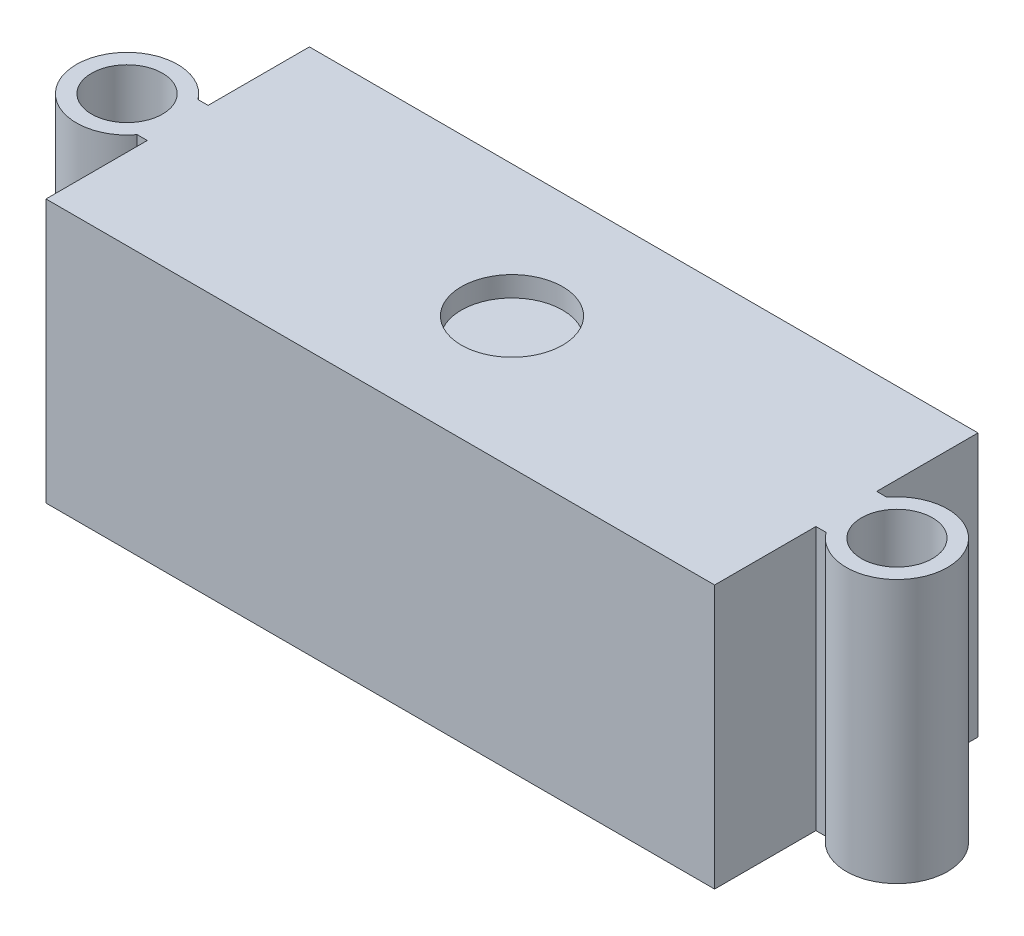
SolidWorks part; units mm, degrees
ref_plane "Front Plane" through (0, 0, 0) normal (0, 0, 1) x (1, 0, 0)
ref_plane "Top Plane" through (0, 0, 0) normal (0, 1, 0) x (1, 0, 0)
ref_plane "Right Plane" through (0, 0, 0) normal (1, 0, 0) x (0, 0, -1)
sketch "Sketch1" plane through (0, 0, 0) normal (0, 0, 1) x (1, 0, 0)
  line L0 (-15, 1.5) -> (-15, 8.5) construction
  line L1 (-15, 0) -> (15, 0)
  line L2 (-15, 0) -> (-15, 1.5)
  line L3 (-15, 10) -> (15, 10)
  line L4 (15, 0) -> (15, 1.5)
  line L5 (-15, 8.5) -> (-15, 10)
  line L6 (15, 1.5) -> (15, 8.5) construction
  line L7 (15, 8.5) -> (15, 10)
  arc A0 (15, 8.5) -> (15, 1.5) centre (15, 5) ccw
  arc A1 (-15, 1.5) -> (-15, 8.5) centre (-15, 5) ccw
  point P5 (0, 0)
  point P12 (0, 0)
  point P13 (0, 0)
  dimension "D3" = 1.5
  dimension "D1" = 10
  dimension "D2" = 30
  dimension "D4" = 1.5
  dimension "D5" = 5
extrude "Boss-Extrude2" add sketch "Sketch1" along normal blind 10
ref_plane "Plane1" through (0, 0, -0.5) normal (0, 0, -1) x (-1, 0, 0)
sketch "Sketch2" plane through (0, 0, -0.5) normal (0, 0, -1) x (-1, 0, 0)
  line L0 (-15.5, 10.5) -> (0, 10.5)
  line L1 (-15.5, 10.5) -> (-15.5, 8)
  line L2 (-15.5, 2) -> (-15.5, -0.5)
  line L3 (-15.5, -0.5) -> (0, -0.5)
  line L4 (-15, 2) -> (-15.5, 2)
  line L5 (-15, 8) -> (-15.5, 8)
  line L6 (15, 0) -> (15, 1.5)
  line L7 (-15, 0) -> (15, 0)
  line L8 (-15, 1.5) -> (-15, 0)
  line L9 (-15, 10) -> (-15, 8.5)
  line L10 (15, 10) -> (-15, 10)
  line L11 (15, 8.5) -> (15, 10)
  line L12 (15, 0) -> (15, 1.5)
  line L13 (-15, 0) -> (15, 0)
  line L14 (-15, 1.5) -> (-15, 0)
  line L15 (-15, 10) -> (-15, 8.5)
  line L16 (15, 10) -> (-15, 10)
  line L17 (15, 8.5) -> (15, 10)
  line L18 (-16.5, -1.5) -> (0, -1.5)
  line L19 (-16.5, 3) -> (-16.5, -1.5)
  line L20 (-15, 3) -> (-16.5, 3)
  line L21 (-15, 7) -> (-16.5, 7)
  line L22 (-16.5, 11.5) -> (-16.5, 7)
  line L23 (-16.5, 11.5) -> (0, 11.5)
  line L24 (0, 5.5) -> (0, -5.5) construction
  line L25 (16.5, 3) -> (16.5, -1.5)
  line L26 (16.5, -1.5) -> (0, -1.5)
  line L27 (15.5, -0.5) -> (0, -0.5)
  line L28 (15.5, 2) -> (15.5, -0.5)
  line L29 (15, 3) -> (16.5, 3)
  line L30 (15, 2) -> (15.5, 2)
  line L31 (15, 7) -> (16.5, 7)
  line L32 (15, 8) -> (15.5, 8)
  line L33 (16.5, 11.5) -> (16.5, 7)
  line L34 (15.5, 10.5) -> (15.5, 8)
  line L35 (16.5, 11.5) -> (0, 11.5)
  line L36 (15.5, 10.5) -> (0, 10.5)
  line L37 (-15.5, -0.5) -> (0.1388, -0.5) construction
  line L38 (-16.5, -1.5) -> (0.1388, -1.5) construction
  line L39 (16.5, 7) -> (16.5, 3)
  line L40 (-16.5, 7) -> (-16.5, 3)
  arc A0 (-15, 2) -> (-15, 8) centre (-15, 5) ccw
  arc A1 (-15, 3) -> (-15, 7) centre (-15, 5) ccw
  arc A2 (-15, 1.5) -> (-15, 8.5) centre (-15, 5) ccw
  arc A3 (15, 8.5) -> (15, 1.5) centre (15, 5) ccw
  arc A4 (-15, 1.5) -> (-15, 8.5) centre (-15, 5) ccw
  arc A5 (15, 8.5) -> (15, 1.5) centre (15, 5) ccw
  arc A6 (15, 3) -> (15, 7) centre (15, 5) cw
  arc A7 (15, 2) -> (15, 8) centre (15, 5) cw
  dimension "D4" = 0.5
  dimension "D7" = 1
  dimension "D2" = 0.5
  dimension "D3" = 0.5
  dimension "D5" = 0.5
  dimension "D6" = 0.5
  dimension "D1" = 0
extrude "Boss-Extrude3" add sketch "Sketch2" against normal blind 11 separate body contours L29 A6 L31 L33 L35 L23 L22 L21 A1 L20 L19 L18 L26 L25 A7 L30 L28 L27 L3 L2 L4 A0 L5 L1 L0 L36 L34 L32 | A6 L29 L39 L31 | L20 A1 L21 L40
sketch "Sketch3" plane through (16.5, 0, 0) normal (1, 0, 0) x (0, 0, -1)
  line L17 (0.5, 11.5) -> (1.5, 11.5)
  line L18 (0.5, 11.5) -> (0.5, -1.5)
  line L19 (0.5, -1.5) -> (1.5, -1.5)
  line L20 (1.5, 11.5) -> (1.5, -1.5)
  line L21 (-10.5, 11.5) -> (-11.5, 11.5)
  line L22 (-10.5, 11.5) -> (-10.5, -1.5)
  line L23 (-10.5, -1.5) -> (-11.5, -1.5)
  line L24 (-11.5, 11.5) -> (-11.5, -1.5)
  point P10 (0, 0)
  dimension "D1" = 1
  dimension "D2" = 1
extrude "Boss-Extrude4" add sketch "Sketch3" against normal blind 33
sketch "Sketch4" plane through (0, 11.5, 0) normal (0, 1, 0) x (1, 0, 0)
  line L0 (-16.5, -11.5) -> (-16.5, 1.5) construction
  line L1 (-16.5, -11.5) -> (-16.5, 1.5) construction
  line L2 (0, -7.15) -> (0, 7.15) construction
  line L3 (16.5, -6.5) -> (17.1, -6.5)
  line L4 (-16.5, -3.5) -> (-17.1, -3.5)
  line L5 (-16.5, -3.5) -> (-16.5, -6.5)
  line L6 (-16.5, -6.5) -> (-17.1, -6.5)
  line L7 (-17.1, -3.5) -> (-17.1, -6.5)
  line L8 (17.1, -3.5) -> (17.1, -6.5)
  line L9 (16.5, -3.5) -> (16.5, -6.5)
  line L10 (16.5, -3.5) -> (17.1, -3.5)
  circle A0 centre (-19, -5) radius 2.5
  circle A1 centre (-19, -5) radius 1.75
  circle A2 centre (19, -5) radius 1.75
  circle A3 centre (19, -5) radius 2.5
  point P5 (-16.5, -5)
  point P15 (0, 0)
  point P16 (-16.8738, -3.0747)
  point P17 (-16.5, -5)
  line M6 (16.5, -11.5) -> (16.5, 1.5)
  line M8 (-16.5, 1.5) -> (-16.5, -11.5)
  dimension "D1" = 5
  dimension "D2" = 3.5
  dimension "D3" = 3
  dimension "D4" = 0.6
extrude "Boss-Extrude5" add sketch "Sketch4" against normal blind 13 contours L4 A0 L6 L7 A1 | L6 A0 L4 L7 | A0 L6 L5 | A0 L4 M8 | A3 L3 L8 L10 | L9 A3 L10 | L3 A3 M6 | A3 L10 L8 L3 A2
sketch "Sketch5" plane through (0, 10, 0) normal (0, 1, 0) x (1, 0, 0)
  line L0 (0, 1.5) -> (0, -11.5) construction
  line L1 (-16.5, 1.5) -> (16.5, 1.5) construction
  line L2 (-16.5, -11.5) -> (16.5, -11.5) construction
  circle A0 centre (0, -5) radius 2.5
  point P9 (0, -5)
  dimension "D1" = 5
extrude "Cut-Extrude1" cut sketch "Sketch5" along normal up to surface (1.5 mm away) up to face at (0, 11.5, 5)
